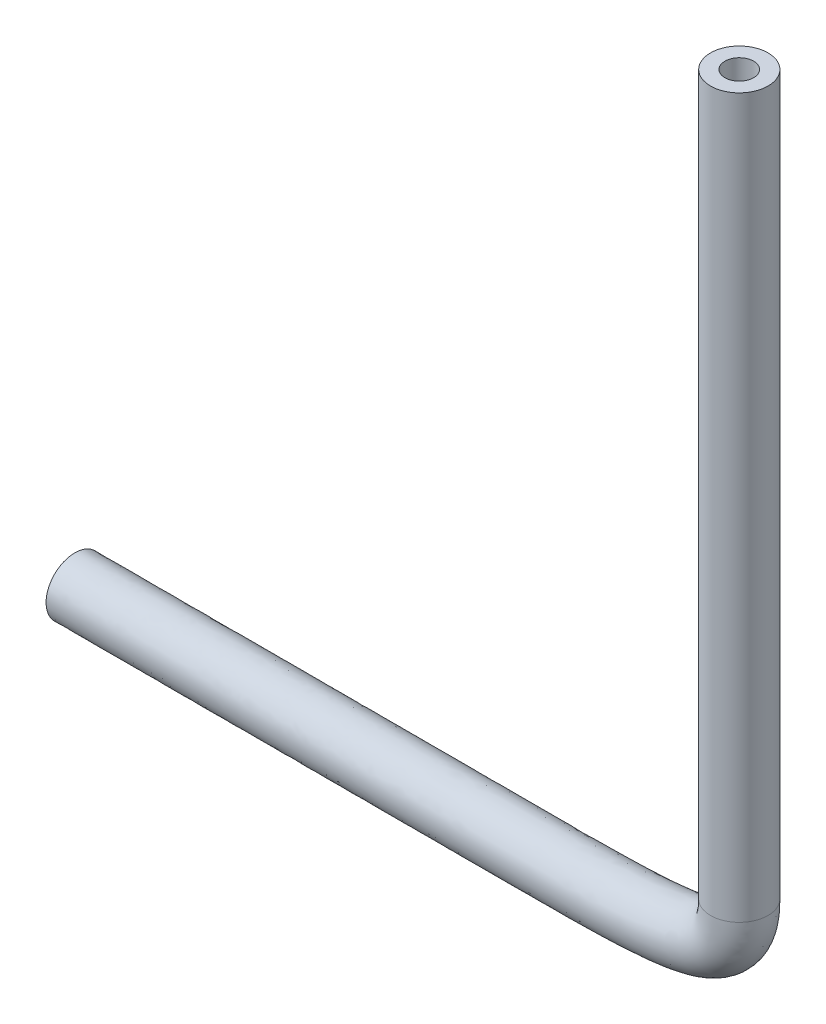
SolidWorks part; units mm, degrees
other "Pipe1"
material "PTFE (general)"
ref_plane "Front" through (0, 0, 0) normal (0, 0, 1) x (1, 0, 0)
ref_plane "Top" through (0, 0, 0) normal (0, 1, 0) x (1, 0, 0)
ref_plane "Right" through (0, 0, 0) normal (1, 0, 0) x (0, 0, -1)
sketch "PipeSke" plane through (0, 0, 0) normal (0, 0, 1) x (1, 0, 0)
  line L0 (0, 0) -> (-12.5, 0)
  line L1 (6, 21.7045) -> (6, 1.7045)
  spline S0 degree 3 poles (0, 0) (4.6199, 0) (6, 0.036) (6, 1.7045) knots 0 0 0 0 1 1 1 1
  dimension "D1" = 12.5
  dimension "D2" = 20
sketch "PipeRing" plane through (0, 0, 0) normal (1, 0, 0) x (0, 0, -1)
  circle A0 centre (0, 0) radius 0.8
  circle A1 centre (0, 0) radius 0.4
  dimension "D1" = 1.6
  dimension "D2" = 0.8
sweep "Pipe" add profiles "PipeRing" path "PipeSke"
